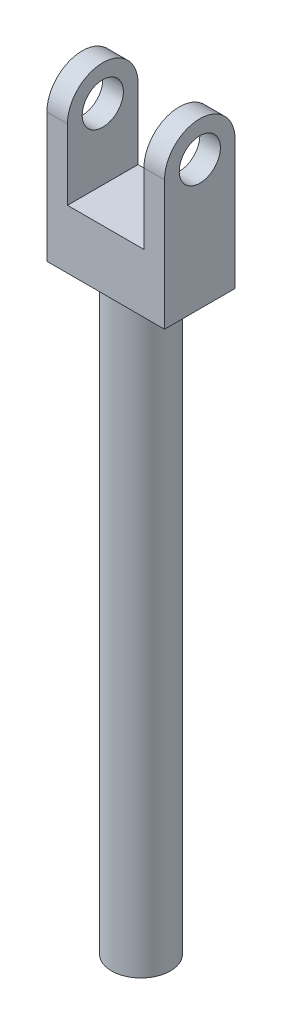
SolidWorks part; units mm, degrees
ref_plane "Plano frontal" through (0, 0, 0) normal (0, 0, 1) x (1, 0, 0)
ref_plane "Plano superior" through (0, 0, 0) normal (0, 1, 0) x (1, 0, 0)
ref_plane "Plano direito" through (0, 0, 0) normal (1, 0, 0) x (0, 0, -1)
sketch "Esboço1" plane through (0, 0, 0) normal (1, 0, 0) x (0, 0, -1)
  line L1 (-6, 0) -> (-6, -22)
  line L2 (6, 0) -> (6, -22)
  line L3 (-6, -22) -> (6, -22)
  arc A0 (6, 0) -> (-6, 0) centre (0, 0) ccw
  circle A1 centre (0, 0) radius 3.5
  dimension "D1" = 12
  dimension "D3" = 7
  dimension "D2" = 22
extrude "Ressalto-extrusão1" add sketch "Esboço1" along normal mid plane 20
sketch "Esboço2" plane through (0, 0, 0) normal (0, 0, 1) x (1, 0, 0)
  line L0 (0, 0) -> (0, -22) construction
  line L1 (10, -22) -> (-10, -22) construction
  line L2 (10, 0) -> (-10, 0) construction
  circle A0 centre (0, -17) radius 3.5
  dimension "D1" = 7
  dimension "D2" = 17
sketch "Esboço3" plane through (0, 0, 0) normal (0, 0, 1) x (1, 0, 0)
  line L0 (0, 6) -> (0, 0) construction
  line L1 (10, 6) -> (-10, 6) construction
  line L2 (0, 0) -> (0, -22) construction
  line L3 (10, -22) -> (-10, -22) construction
  line L6 (-6.5, 6) -> (6.5, 6)
  line L7 (-6.5, 6) -> (-6.5, -12)
  line L8 (6.5, 6) -> (6.5, -12)
  line L9 (-6.5, -12) -> (6.5, -12)
  dimension "D1" = 6.5
  dimension "D2" = 12
extrude "Corte-extrusão2" cut sketch "Esboço3" against normal mid plane 20
sketch "Esboço4" plane through (0, -22, 0) normal (0, -1, 0) x (1, 0, 0)
  line L0 (0, 6) -> (0, -6) construction
  line L1 (10, 6) -> (-10, 6) construction
  line L2 (10, -6) -> (-10, -6) construction
  line L3 (10, 0) -> (-10, 0) construction
  line L4 (10, 6) -> (10, -6) construction
  line L5 (-10, 6) -> (-10, -6) construction
  circle A0 centre (0, 0) radius 5
  dimension "D1" = 10
extrude "Ressalto-extrusão2" add sketch "Esboço4" along normal blind 100
